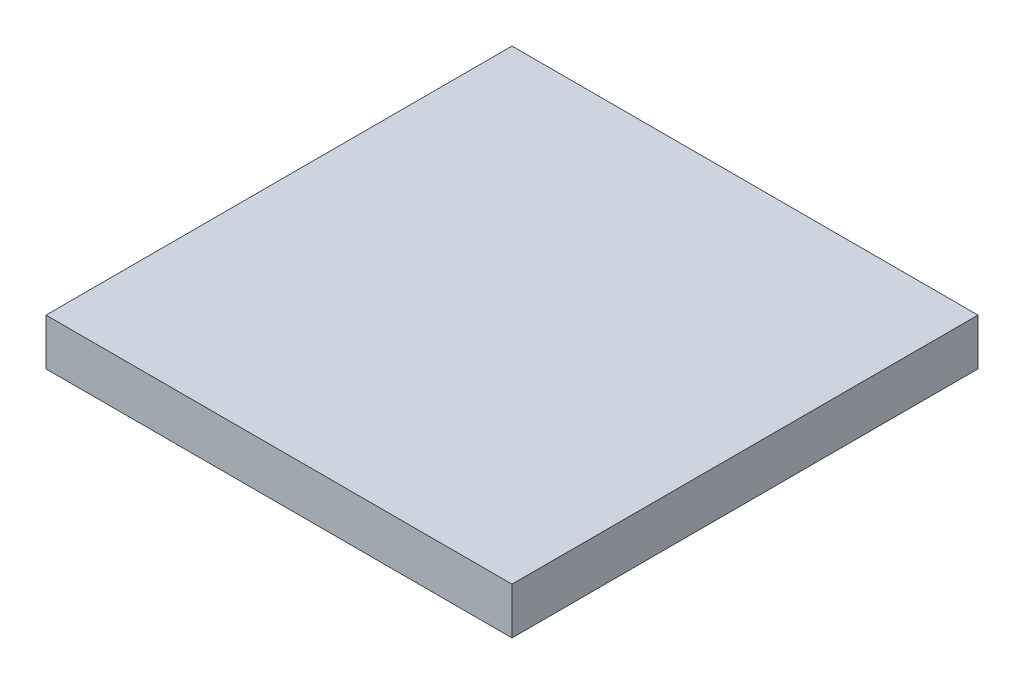
SolidWorks part; units mm, degrees
material "玻璃"
ref_plane "前视基准面" through (0, 0, 0) normal (0, 0, 1) x (1, 0, 0)
ref_plane "上视基准面" through (0, 0, 0) normal (0, 1, 0) x (1, 0, 0)
ref_plane "右视基准面" through (0, 0, 0) normal (1, 0, 0) x (0, 0, -1)
sketch "草图1" plane through (0, 0, 0) normal (0, 1, 0) x (1, 0, 0)
  line L0 (0, 18.6821) -> (0, -15.6404) construction
  line L1 (-10, 10) -> (10, 10)
  line L2 (-10, 10) -> (-10, -10)
  line L3 (-10, -10) -> (10, -10)
  line L4 (10, 10) -> (10, -10)
  line L5 (-19.3464, 0) -> (21.3545, 0) construction
  point P10 (-10, 0)
  point P11 (0, 10)
  dimension "D1" = 20
extrude "凸台-拉伸1" add sketch "草图1" along normal blind 2
